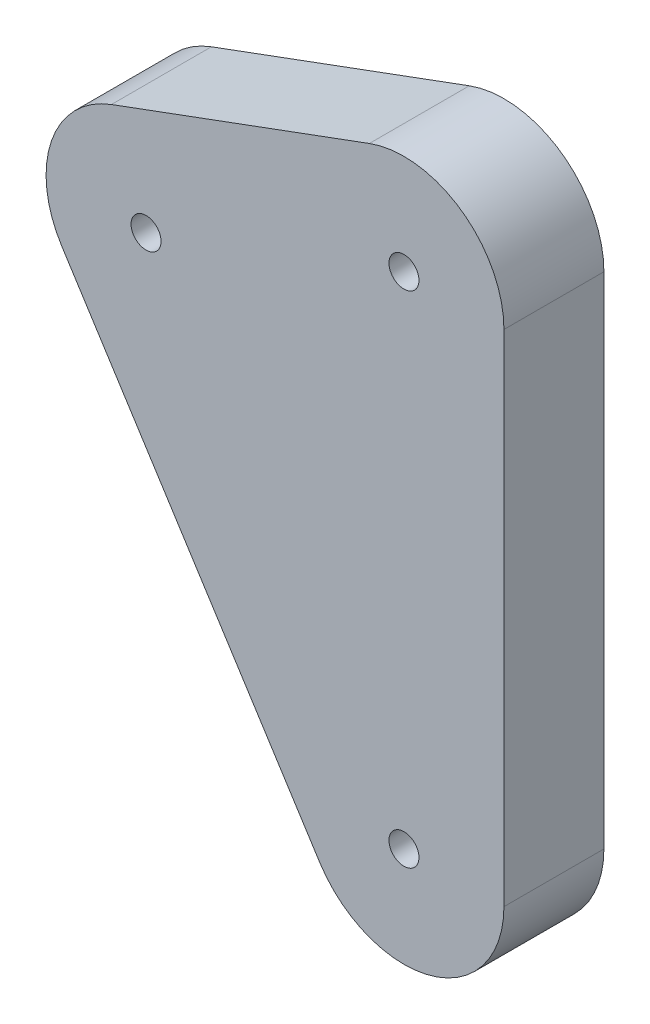
SolidWorks part; units mm, degrees
material "PVC Rigid"
ref_plane "Front Plane" through (0, 0, 0) normal (0, 0, 1) x (1, 0, 0)
ref_plane "Top Plane" through (0, 0, 0) normal (0, 1, 0) x (1, 0, 0)
ref_plane "Right Plane" through (0, 0, 0) normal (1, 0, 0) x (0, 0, -1)
sketch "Sketch1" plane through (0, 0, 0) normal (0, 0, 1) x (1, 0, 0)
  line L3 (-29.2614, 49.8588) -> (-3.4627, 59.3813)
  line L4 (10, 50) -> (10, 0)
  line L5 (-8.4328, -5.3747) -> (-34.2315, 35.1028)
  arc A0 (10, 50) -> (-3.4627, 59.3813) centre (0, 50) ccw
  arc A1 (-29.2614, 49.8588) -> (-34.2315, 35.1028) centre (-25.7987, 40.4775) ccw
  arc A2 (-8.4328, -5.3747) -> (10, 0) centre (0, 0) ccw
  circle A3 centre (-25.7987, 40.4775) radius 1.5
  circle A4 centre (0, 50) radius 1.5
  circle A5 centre (0, 0) radius 1.5
  dimension "D4" = 20
  dimension "D5" = 20
  dimension "D6" = 20
  dimension "D7" = 3
  dimension "D8" = 3
  dimension "D9" = 3
  dimension "D1" = 50
  dimension "D2" = 27.5
  dimension "D3" = 48
extrude "Boss-Extrude1" add sketch "Sketch1" along normal blind 10
